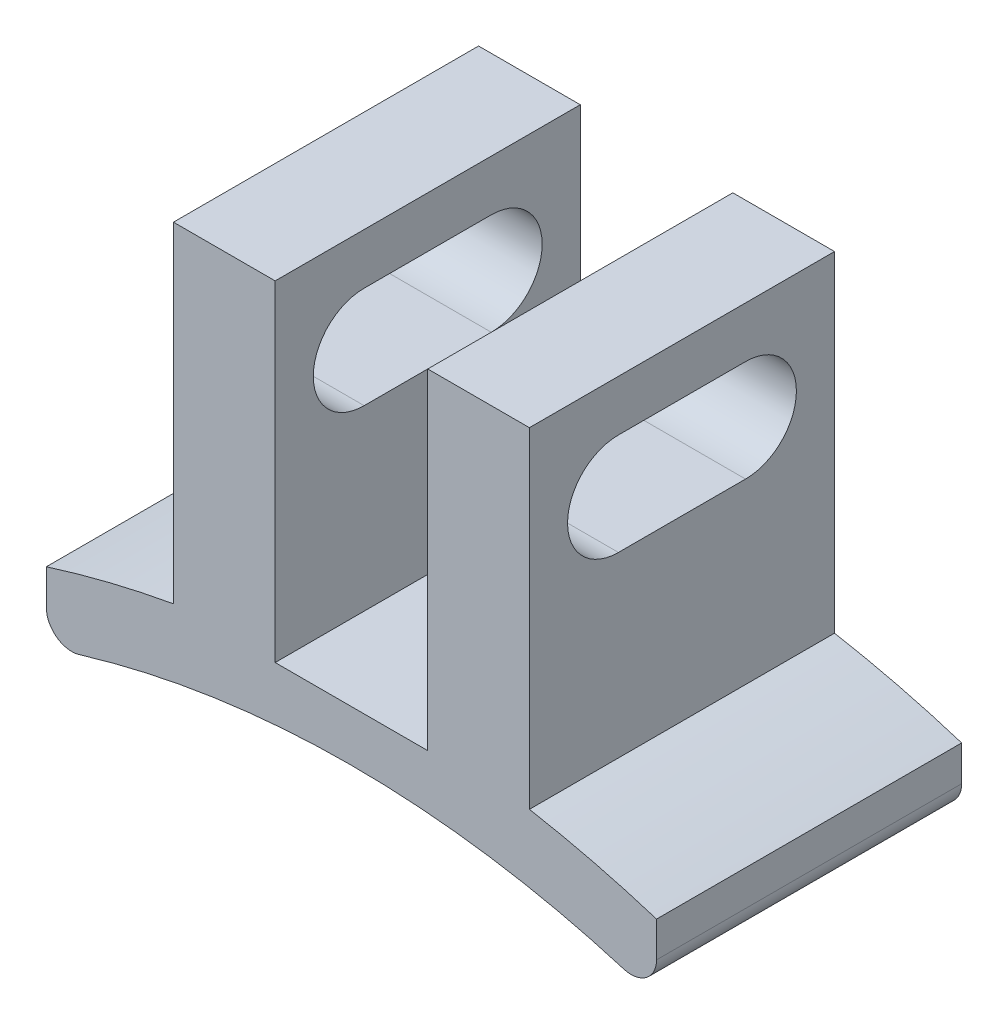
SolidWorks part; units mm, degrees
ref_plane "Front Plane" through (0, 0, 0) normal (0, 0, 1) x (1, 0, 0)
ref_plane "Top Plane" through (0, 0, 0) normal (0, 1, 0) x (1, 0, 0)
ref_plane "Right Plane" through (0, 0, 0) normal (1, 0, 0) x (0, 0, -1)
sketch "Sketch1" plane through (0, 0, 0) normal (0, 0, 1) x (1, 0, 0)
  line L3 (0, 1) -> (0, -1) construction
  line L4 (-6, -1) -> (6, -1)
  line L5 (-6, -1) -> (-6, 1)
  line L6 (-6, 1) -> (-3.5, 1)
  line L7 (6, -1) -> (6, 1)
  line L16 (1.5, 7.5) -> (3.5, 7.5)
  line L17 (1.5, 7.5) -> (1.5, 1)
  line L19 (3.5, 7.5) -> (3.5, 1)
  line L20 (1.5, 7.5) -> (3.5, 1) construction
  line L21 (1.5, 1) -> (3.5, 7.5) construction
  line L23 (-3.5, 7.5) -> (-3.5, 1)
  line L24 (-1.5, 7.5) -> (-3.5, 7.5)
  line L25 (-1.5, 7.5) -> (-1.5, 1)
  line L27 (3.5, 1) -> (6, 1)
  line L28 (-1.5, 1) -> (1.5, 1)
  point P0 (0, 1)
  point P8 (0, -1)
  point P12 (2.5, 4.25)
  point P27 (0, 0)
  dimension "D1" = 3
  dimension "D2" = 2
  dimension "D3" = 12
  dimension "D4" = 6.5
extrude "Boss-Extrude1" add sketch "Sketch1" along normal mid plane 6
sketch "Sketch5" plane through (-3.5, 0, 0) normal (-1, 0, 0) x (0, 0, 1)
  line L0 (-3, 7.5) -> (-3, 1) construction
  line L1 (1.25, 4.5) -> (-1.25, 4.5)
  line L2 (1.25, 4.5) -> (1.25, 6.5) construction
  line L3 (1.25, 6.5) -> (-1.25, 6.5)
  line L5 (1.25, 4.5) -> (-1.25, 6.5) construction
  line L6 (1.25, 6.5) -> (-1.25, 4.5) construction
  line L7 (3, 7.5) -> (-3, 7.5) construction
  line L8 (0, 6.5) -> (0, 4.5) construction
  arc A0 (-1.25, 4.5) -> (-1.25, 6.5) centre (-1.25, 5.5) cw
  arc A1 (1.25, 4.5) -> (1.25, 6.5) centre (1.25, 5.5) ccw
  point P0 (0, 5.5)
  point P4 (-1.2881, 6.5)
  point P18 (-2.25, 5.5)
  point P19 (2.25, 5.5)
  point P21 (-1.2095, 4.5)
  dimension "D2" = 1
  dimension "D3" = 2
  dimension "D4" = 0.75
extrude "Cut-Extrude4" cut sketch "Sketch5" against normal through all both and the other way through all
sketch "Sketch6" plane through (0, 0, 3) normal (0, 0, 1) x (1, 0, 0)
  line L0 (-6, 1) -> (-3.5, 1)
  line L1 (-6, 1) -> (-6, 0.3812)
  line L2 (-6, 1) -> (-6, -1) construction
  line L3 (3.5, 1) -> (6, 1)
  line L4 (6, 1) -> (6, 0.3812)
  line L5 (6, -1) -> (6, 1) construction
  circle A0 centre (0, -18.5) radius 18.5
  arc A1 (-3.5, 1) -> (-6, 0.3812) centre (0, -18.5) ccw
  arc A2 (6, 0.3812) -> (3.5, 1) centre (0, -18.5) ccw
extrude "Cut-Extrude5" cut sketch "Sketch6" against normal through all both and the other way through all
fillet "Fillet1" radius 0.5 2 edges at (6, -1, 0) (-6, -1, 0)
